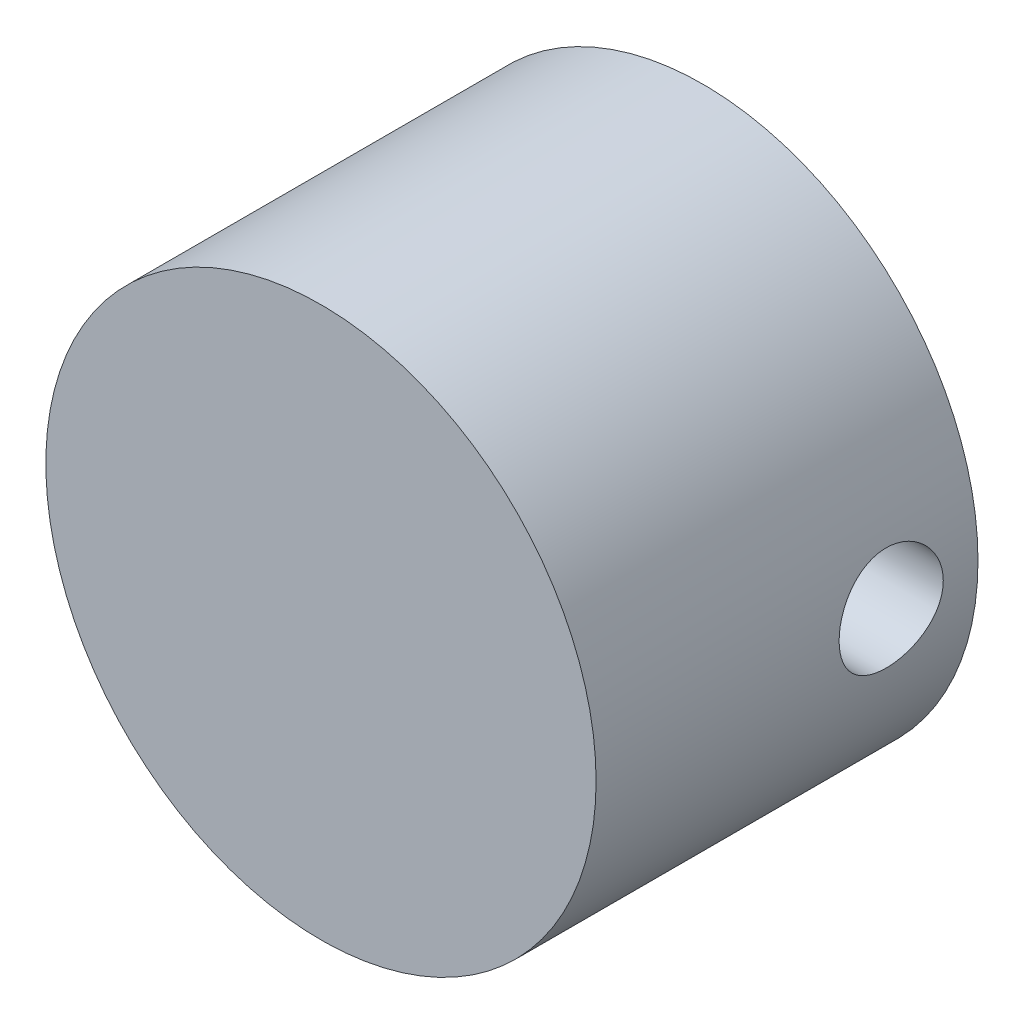
SolidWorks part; units mm, degrees
ref_plane "Front" through (0, 0, 0) normal (0, 0, 1) x (1, 0, 0)
ref_plane "Top" through (0, 0, 0) normal (0, 1, 0) x (1, 0, 0)
ref_plane "Right" through (0, 0, 0) normal (1, 0, 0) x (0, 0, -1)
sketch "Sketch1" plane through (0, 0, 0) normal (0, 0, 1) x (1, 0, 0)
  circle A0 centre (0, 0) radius 7.925
extrude "Extrude1" add sketch "Sketch1" along normal blind 11
sketch "Sketch2" plane through (0, 0, 0) normal (1, 0, 0) x (0, 0, -1)
  line L0 (-11, 0) -> (0, 0) construction
  circle A0 centre (-2.5, 0) radius 1.5
extrude "Cut-Extrude1" cut sketch "Sketch2" against normal through all and the other way through all
